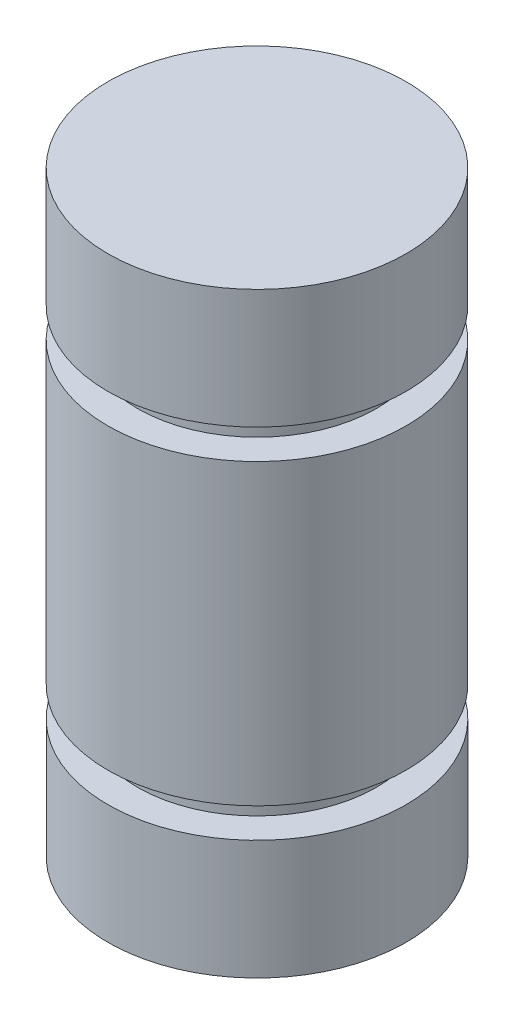
SolidWorks part; units mm, degrees
ref_plane "Front Plane" through (0, 0, 0) normal (0, 0, 1) x (1, 0, 0)
ref_plane "Top Plane" through (0, 0, 0) normal (0, 1, 0) x (1, 0, 0)
ref_plane "Right Plane" through (0, 0, 0) normal (1, 0, 0) x (0, 0, -1)
sketch "Sketch1" plane through (0, 0, 0) normal (0, 1, 0) x (1, 0, 0)
  circle A0 centre (0, 0) radius 6.35
  dimension "D1" = 12.7
extrude "Boss-Extrude2" add sketch "Sketch1" along normal blind 12.7
sketch "Sketch4" plane through (0, 12.7, 0) normal (0, 1, 0) x (1, 0, 0)
  circle A0 centre (0, 0) radius 5.08
  dimension "D1" = 10.16
extrude "Boss-Extrude3" add sketch "Sketch4" along normal blind 1.27
sketch "Sketch5" plane through (0, 13.97, 0) normal (0, 1, 0) x (1, 0, 0)
  circle A0 centre (0, 0) radius 6.35
  dimension "D1" = 12.7
extrude "Boss-Extrude4" add sketch "Sketch5" along normal blind 5.08
sketch "Sketch6" plane through (0, 0, 0) normal (0, -1, 0) x (1, 0, 0)
  circle A0 centre (0, 0) radius 5.08
  dimension "D1" = 10.16
extrude "Boss-Extrude5" add sketch "Sketch6" along normal blind 1.27
sketch "Sketch7" plane through (0, -1.27, 0) normal (0, -1, 0) x (1, 0, 0)
  circle A0 centre (0, 0) radius 6.35
  dimension "D1" = 12.7
extrude "Boss-Extrude6" add sketch "Sketch7" along normal blind 5.08
